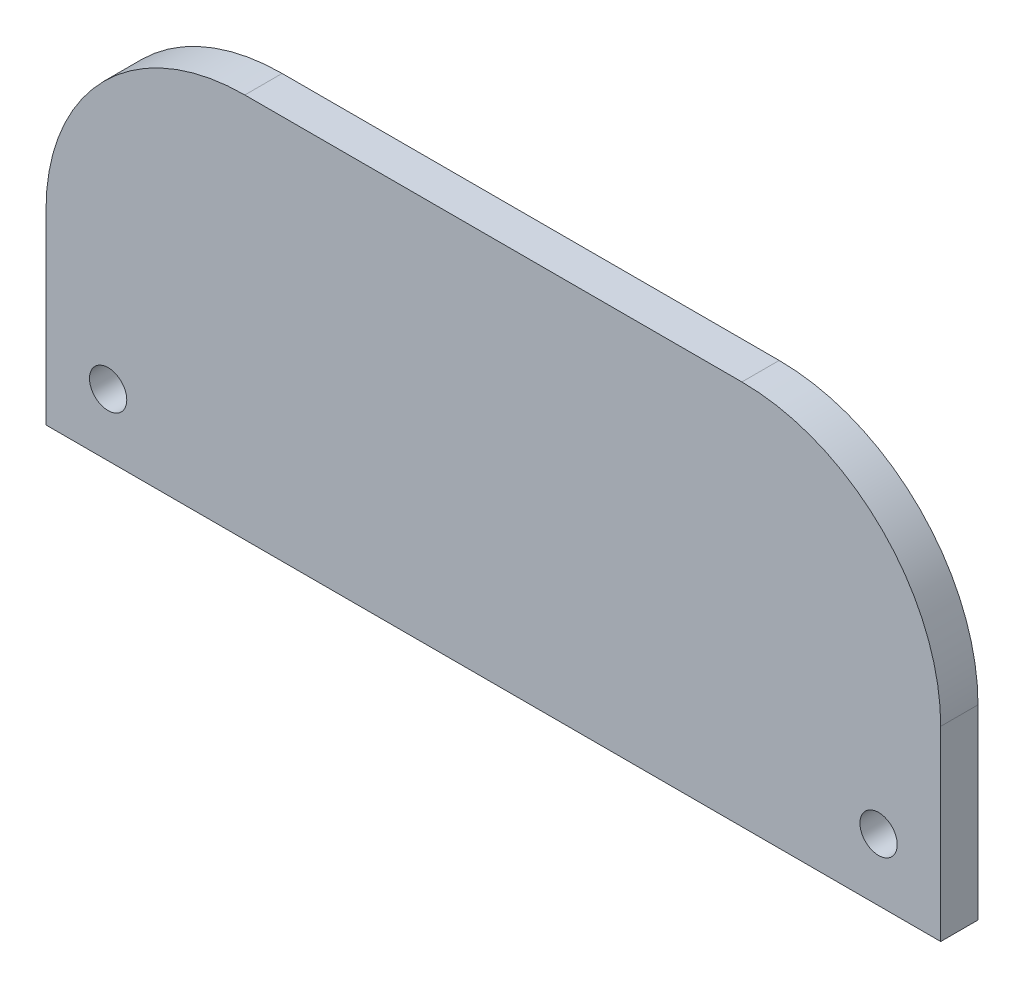
SolidWorks part; units mm, degrees
ref_plane "Front Plane" through (0, 0, 0) normal (0, 0, 1) x (1, 0, 0)
ref_plane "Top Plane" through (0, 0, 0) normal (0, 1, 0) x (1, 0, 0)
ref_plane "Right Plane" through (0, 0, 0) normal (1, 0, 0) x (0, 0, -1)
sketch "Sketch1" plane through (0, 0, 0) normal (0, 0, 1) x (1, 0, 0)
  line L1 (0, 0) -> (70, 0)
  line L2 (0, 0) -> (0, 70)
  line L3 (0, 70) -> (70, 70)
  line L4 (70, 0) -> (70, 70)
  dimension "D1" = 70
  dimension "D2" = 70
extrude "Boss-Extrude1" add sketch "Sketch1" along normal blind 10
sketch "Sketch2" plane through (0, 0, 10) normal (0, 0, 1) x (1, 0, 0)
  line L0 (70, 70) -> (0, 70) construction
  circle A0 centre (35, 49) radius 12
  circle A1 centre (19.5, 65) radius 2
  circle A2 centre (50.5, 65) radius 2
  circle A3 centre (19.5, 34) radius 2
  circle A4 centre (50.5, 34) radius 2
  circle A5 centre (15, 15) radius 11.5
  circle A6 centre (55, 15) radius 11.5
  point P17 (35, 70)
  dimension "D1" = 24
  dimension "D2" = 4
  dimension "D3" = 4
  dimension "D4" = 4
  dimension "D5" = 4
  dimension "D15" = 23
  dimension "D16" = 23
  dimension "D6" = 21
  dimension "D7" = 5
  dimension "D8" = 5
  dimension "D9" = 31
  dimension "D10" = 31
  dimension "D11" = 31
  dimension "D12" = 31
  dimension "D13" = 15.5
  dimension "D14" = 0
  dimension "D17" = 40
  dimension "D18" = 15
  dimension "D19" = 15
  dimension "D20" = 15
extrude "Cut-Extrude1" cut sketch "Sketch2" against normal blind 10
sketch "Sketch3" plane through (0, 0, 0) normal (-1, 0, 0) x (0, 0, 1)
  line L1 (0, 70) -> (10, 70)
  line L2 (0, 70) -> (0, 0)
  line L3 (0, 0) -> (10, 0)
  line L4 (10, 70) -> (10, 0)
extrude "Boss-Extrude2" add sketch "Sketch3" along normal blind 15
sketch "Sketch4" plane through (70, 0, 0) normal (1, 0, 0) x (0, 0, -1)
  line L1 (0, 70) -> (-10, 70)
  line L2 (0, 70) -> (0, 0)
  line L3 (0, 0) -> (-10, 0)
  line L4 (-10, 70) -> (-10, 0)
extrude "Boss-Extrude3" add sketch "Sketch4" along normal blind 15 contours L4 L3 L2 L1
sketch "Sketch5" plane through (0, 0, 10) normal (0, 0, 1) x (1, 0, 0)
  circle A0 centre (15, 15) radius 11.5
  circle A1 centre (55, 15) radius 11.5
  circle A2 centre (15, 15) radius 4
  circle A3 centre (55, 15) radius 4
  dimension "D1" = 8
  dimension "D2" = 8
extrude "Boss-Extrude4" add sketch "Sketch5" against normal blind 2
sketch "Sketch6" plane through (0, 0, 0) normal (0, 0, -1) x (-1, 0, 0)
  line L0 (-85, 70) -> (-85, 0) construction
  line L1 (-85, 70) -> (15, 70) construction
  circle A0 centre (-80, 65) radius 1.5
  circle A1 centre (-80, 5) radius 1.5
  circle A2 centre (10, 65) radius 1.6487
  circle A3 centre (10, 5) radius 1.5
  dimension "D4" = 3
  dimension "D5" = 3
  dimension "D8" = 3
  dimension "D1" = 5
  dimension "D2" = 5
  dimension "D3" = 5
  dimension "D6" = 5
  dimension "D7" = 5
extrude "Cut-Extrude3" cut sketch "Sketch6" against normal blind 10
sketch "Sketch7" plane through (0, 0, 0) normal (0, 0, -1) x (-1, 0, 0)
  circle A0 centre (-35, 49) radius 11.9867
  circle A1 centre (-50.5, 65) radius 2
  circle A2 centre (-19.5, 65) radius 2
  circle A3 centre (-19.5, 34) radius 2
  circle A4 centre (-50.5, 34) radius 2
extrude "Boss-Extrude5" add sketch "Sketch7" against normal blind 10
sketch "Sketch8" plane through (0, 0, 0) normal (0, 0, -1) x (-1, 0, 0)
  line L0 (-85, 70) -> (15, 70) construction
  circle A0 centre (-33.9287, 49) radius 12
  circle A3 centre (-55, 15) radius 4 construction
  dimension "D1" = 24
  dimension "D2" = 21
  dimension "D3" = 40
extrude "Cut-Extrude4" cut sketch "Sketch8" against normal blind 10
sketch "Sketch9" plane through (0, 0, 0) normal (0, 0, -1) x (-1, 0, 0)
  circle A0 centre (-49.4287, 64.5) radius 2
  arc A1 (-34.4643, 37.012) -> (-34.4643, 60.988) centre (-33.9287, 49) ccw construction
  circle A2 centre (-49.4287, 33.5) radius 2
  circle A3 centre (-18.4287, 33.5) radius 2
  circle A4 centre (-18.4287, 64.5) radius 2
  point P5 (-21.9287, 49)
  dimension "D3" = 4
  dimension "D5" = 4
  dimension "D6" = 4
  dimension "D8" = 4
  dimension "D1" = 15.5
  dimension "D2" = 15.5
  dimension "D4" = 31
  dimension "D7" = 31
extrude "Cut-Extrude5" cut sketch "Sketch9" against normal blind 10
sketch "Sketch14" plane through (0, 0, 0) normal (0, 0, -1) x (-1, 0, 0)
  line L0 (-85, 0) -> (-85, 70)
  line L1 (-85, 70) -> (15, 70)
  line L2 (15, 70) -> (15, 0)
  line L3 (15, 70) -> (15, 0) construction
  line L4 (15, 0) -> (-85, 0) construction
  line L5 (-71, 15) -> (-71, 0)
  line L6 (-71, 0) -> (-85, 0)
  line L7 (-39, 15) -> (-39, 0)
  line L8 (-39, 0) -> (-31, 0)
  line L9 (-31, 0) -> (-31, 15)
  line L10 (1, 15) -> (1, 0)
  line L11 (1, 0) -> (15, 0)
  arc A0 (-31, 15) -> (1, 15) centre (-15, 15) cw
  arc A1 (-39, 15) -> (-71, 15) centre (-55, 15) ccw
  dimension "D1" = 16
  dimension "D2" = 16
extrude "Cut-Extrude7" cut sketch "Sketch14" against normal blind 5 contours L2 L11 L10 A0 L9 L8 L7 A1 L5 L6 L0 L1
sketch "Sketch15" plane through (0, 0, 5) normal (0, 0, -1) x (-1, 0, 0)
  line L1 (-71, 0) -> (-85, 0)
  line L2 (-71, 0) -> (-71, 70)
  line L3 (-71, 70) -> (-85, 70)
  line L4 (-85, 0) -> (-85, 70)
  line L5 (1, 0) -> (15, 0)
  line L6 (1, 0) -> (1, 70)
  line L7 (1, 70) -> (15, 70)
  line L8 (15, 0) -> (15, 70)
extrude "Cut-Extrude8" cut sketch "Sketch15" against normal blind 5
sketch "Sketch16" plane through (0, 0, 5) normal (0, 0, -1) x (-1, 0, 0)
  line L0 (-71, 70) -> (1, 70) construction
  line L1 (-71, 15) -> (-71, 70) construction
  line L2 (-39, 0) -> (-71, 0) construction
  line L4 (1, 15) -> (1, 0) construction
  circle A0 centre (-66, 65) radius 1.5
  circle A1 centre (-66, 5) radius 1.5
  circle A2 centre (-4, 5) radius 1.5
  circle A3 centre (-4, 65) radius 1.5
  dimension "D1" = 3
  dimension "D5" = 3
  dimension "D6" = 3
  dimension "D8" = 3
  dimension "D2" = 5
  dimension "D3" = 5
  dimension "D4" = 5
  dimension "D7" = 5
extrude "Cut-Extrude9" cut sketch "Sketch16" along normal blind 19 and the other way blind 48
sketch "Sketch17" plane through (0, 0, 8) normal (0, 0, -1) x (-1, 0, 0)
  circle A0 centre (-15, 15) radius 5
  circle A1 centre (-55, 15) radius 5
  dimension "D1" = 10
  dimension "D2" = 10
extrude "Cut-Extrude10" cut sketch "Sketch17" against normal blind 19
sketch "Sketch18" plane through (0, 0, 5) normal (0, 0, -1) x (-1, 0, 0)
  line L0 (-71, 70) -> (1, 70) construction
  line L1 (-59.5583, 70) -> (-15, 70)
  line L2 (-59.5583, 70) -> (-59.5583, 31)
  line L3 (-59.5583, 31) -> (-15, 31)
  line L4 (-15, 70) -> (-15, 31)
  arc A0 (1, 15) -> (-31, 15) centre (-15, 15) ccw construction
extrude "Boss-Extrude6" add sketch "Sketch18" against normal blind 5
sketch "Sketch19" plane through (0, 0, 10) normal (0, 0, 1) x (1, 0, 0)
  line L0 (71, 15) -> (71, 0)
  line L1 (71, 0) -> (-1, 0)
  line L2 (-1, 0) -> (-1, 15)
  line L3 (15, 31) -> (55, 31)
  arc A0 (31, 15) -> (-1, 15) centre (15, 15) ccw construction
  arc A1 (71, 15) -> (39, 15) centre (55, 15) ccw construction
  arc A2 (71, 15) -> (55, 31) centre (55, 15) ccw
  arc A3 (15, 31) -> (-1, 15) centre (15, 15) ccw
  circle A4 centre (66, 5) radius 1.5
  circle A5 centre (4, 5) radius 1.5
  line M2 (-1, 70) -> (-1, 0)
  line M3 (-1, 0) -> (71, 0)
  line M4 (71, 0) -> (71, 70)
  circle M5 centre (55, 15) radius 5
  circle M6 centre (15, 15) radius 5
  circle M7 centre (66, 5) radius 1.5
  circle M8 centre (4, 5) radius 1.5
extrude "Boss-Extrude7" add sketch "Sketch19" along normal blind 3 contours L3 A3 A2 M2 M3 M4 M6 M8 M7 M5 | M5 | M6
sketch "Sketch20" plane through (0, 70, 0) normal (0, 1, 0) x (1, 0, 0)
  line L1 (71, -10) -> (-1, -10)
  line L2 (71, -10) -> (71, 0)
  line L3 (71, 0) -> (-1, 0)
  line L4 (-1, -10) -> (-1, 0)
extrude "Cut-Extrude11" cut sketch "Sketch20" against normal blind 77
